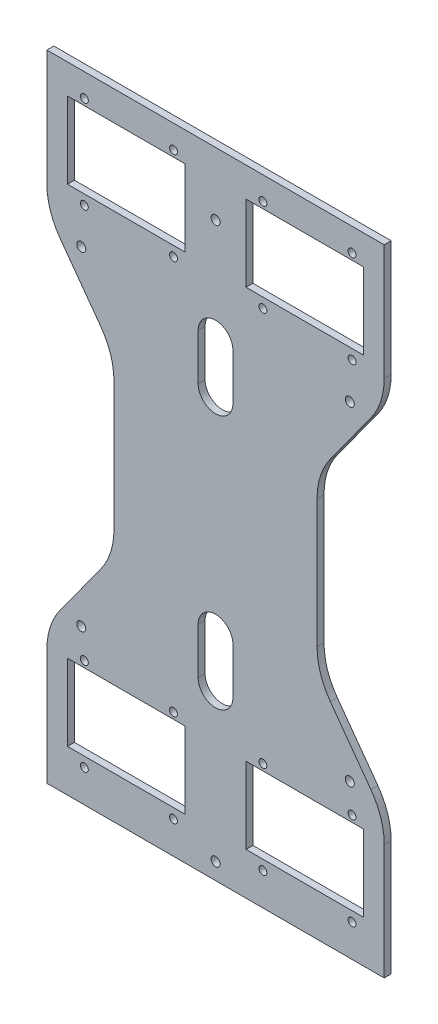
SolidWorks part; units mm, degrees
ref_plane "Alzado" through (0, 0, 0) normal (0, 0, 1) x (1, 0, 0)
ref_plane "Planta" through (0, 0, 0) normal (0, 1, 0) x (1, 0, 0)
ref_plane "Vista lateral" through (0, 0, 0) normal (1, 0, 0) x (0, 0, -1)
sketch "Croquis1" plane through (0, 0, 0) normal (0, 0, 1) x (1, 0, 0)
  line L1 (72.8628, -137.1535) -> (-72.8628, -137.1535)
  line L2 (72.8628, -137.1535) -> (72.8628, -77.4151)
  line L3 (72.8628, 137.1535) -> (-72.8628, 137.1535)
  line L4 (-72.8628, -137.1535) -> (-72.8628, -77.4151)
  line L5 (72.8628, -137.1535) -> (-72.8628, 137.1535) construction
  line L6 (72.8628, 137.1535) -> (-72.8628, -137.1535) construction
  line L7 (-72.8628, 0) -> (72.8628, 0) construction
  line L8 (0, -137.1535) -> (0, 137.1535) construction
  line L9 (-43.8628, -37.5) -> (-43.8628, 37.5)
  line L10 (-43.8628, 37.5) -> (-72.8628, 77.4151)
  line L11 (-43.8628, -37.5) -> (-72.8628, -77.4151)
  line L12 (43.8628, -37.5) -> (72.8628, -77.4151)
  line L13 (43.8628, -37.5) -> (43.8628, 37.5)
  line L14 (43.8628, 37.5) -> (72.8628, 77.4151)
  line L15 (-72.8628, 77.4151) -> (-72.8628, 137.1535)
  line L16 (72.8628, 77.4151) -> (72.8628, 137.1535)
  point P0 (0, 0)
  point P11 (0, 0)
  point P14 (-43.8628, 0)
  dimension "D1" = 145.7256
  dimension "D2" = 274.3069
  dimension "D3" = 144
  dimension "D4" = 144
  dimension "D5" = 29
  dimension "D6" = 75
  dimension "D7" = 137.1535
extrude "Saliente-Extruir1" add sketch "Croquis1" along normal blind 3
fillet "Redondeo1" radius 30 8 edges at (72.8628, 77.4151, 1.5) (43.8628, 37.5, 1.5) (43.8628, -37.5, 1.5) (72.8628, -77.4151, 1.5) (-43.8628, -37.5, 1.5) (-72.8628, -77.4151, 1.5) (-43.8628, 37.5, 1.5) (-72.8628, 77.4151, 1.5)
sketch "mid bores" plane through (0, 0, 0) normal (0, 0, 1) x (1, 0, 0)
  point P0 (-58, 71)
  point P1 (0, 110)
  point P2 (58, 71)
  point P4 (0, -130)
  point P5 (58, -71)
  point P7 (-58, -71)
  dimension "D1" = 71
  dimension "D2" = 110
  dimension "D3" = 58
  dimension "D6" = 130
  dimension "D4" = 2
  dimension "D5" = 2
sketch "Croquis2" plane through (0, 0, 3) normal (0, 0, 1) x (1, 0, 0)
  line L0 (0, 45) -> (0, 65) construction
  line L1 (-7.5, 45) -> (-7.5, 65)
  line L2 (7.5, 45) -> (7.5, 65)
  arc A0 (-7.5, 45) -> (7.5, 45) centre (0, 45) ccw
  arc A1 (7.5, 65) -> (-7.5, 65) centre (0, 65) ccw
  point P2 (0, 55)
  point P7 (-3.1499, 63.1879)
  point P8 (0, 0)
  dimension "D1" = 15
  dimension "D2" = 20
  dimension "D3" = 55
extrude "Cortar-Extruir1" cut sketch "Croquis2" against normal through all
mirror "Simetría1" about plane through (0, 0, 0) normal (0, 1, 0) of "Cortar-Extruir1"
sketch "ibt2 bores" plane through (0, 0, 3) normal (0, 0, 1) x (1, 0, 0)
  point P0 (-18.1628, 127.1535)
  point P1 (-18.1628, 87.1535)
  point P2 (-56.6628, 87.1535)
  point P3 (20.4628, 127.1535)
  point P4 (-56.6628, 127.1535)
  point P5 (20.4628, 87.1535)
  point P6 (58.9628, 87.1535)
  point P7 (58.9628, 127.1535)
  point P8 (20.4628, -123.1535)
  point P9 (58.9628, -123.1535)
  point P10 (-18.1628, -123.1535)
  point P11 (-56.6628, -123.1535)
  point P12 (-56.6628, -83.1535)
  point P13 (-18.1628, -83.1535)
  point P14 (20.4628, -83.1535)
  point P15 (58.9628, -83.1535)
hole_wizard "Taladro de margen para M31" positions "Croquis13" profile "Croquis15" hole size "M3" standard "Ansi Metric" end condition through all
sketch "Croquis13" plane through (0, 0, 3) normal (0, 0, 1) x (1, 0, 0)
  point P0 (-56.6628, 127.1535)
  point P3 (-18.1628, 127.1535)
  point P6 (-18.1628, 87.1535)
  point P9 (-56.6628, 87.1535)
  point P14 (20.4628, 127.1535)
  point P17 (20.4628, 87.1535)
  point P20 (58.9628, 87.1535)
  point P23 (58.9628, 127.1535)
  point P27 (58.9628, -123.1535)
  point P30 (20.4628, -123.1535)
  point P33 (20.4628, -83.1535)
  point P36 (58.9628, -83.1535)
  point P39 (-18.1628, -123.1535)
  point P42 (-56.6628, -123.1535)
  point P45 (-56.6628, -83.1535)
  point P48 (-18.1628, -83.1535)
sketch "Croquis15" plane through (-56.6628, 127.1535, 3) normal (1, 0, 0) x (0, -1, 0)
  line L0 (0, 0) -> (0, 3)
  line L1 (0, 3) -> (1.7, 3)
  line L2 (1.7, 3) -> (1.7, 0)
  line L5 (1.7, 0) -> (0, 0)
  line L11 (0, -6.35) -> (0, 107.95) construction
  dimension "Diámetro de taladro hasta el siguiente" = 3.4
  dimension "Profundidad de taladro hasta el siguiente" = 3
sketch "Croquis16" plane through (0, 0, 0) normal (0, 0, -1) x (-1, 0, 0)
  line L0 (13.5628, 124.0035) -> (63.5628, 124.0035) construction
  line L1 (63.5628, 124.0035) -> (63.5628, 91.8035) construction
  line L2 (63.5628, 91.8035) -> (13.5628, 91.8035) construction
  line L3 (13.5628, 91.8035) -> (13.5628, 124.0035) construction
  line L4 (-13.5628, 124.0035) -> (-13.5628, 91.8035) construction
  line L5 (-13.5628, 91.8035) -> (-63.5628, 91.8035) construction
  line L6 (-63.5628, 91.8035) -> (-63.5628, 124.0035) construction
  line L7 (-63.5628, 124.0035) -> (-13.5628, 124.0035) construction
  line L8 (-63.9628, 124.4035) -> (-13.1628, 124.4035)
  line L9 (-13.1628, 124.4035) -> (-13.1628, 91.4035)
  line L10 (-13.1628, 91.4035) -> (-63.9628, 91.4035)
  line L11 (-63.9628, 91.4035) -> (-63.9628, 124.4035)
  line L12 (13.1628, 91.4035) -> (13.1628, 124.4035)
  line L13 (13.1628, 124.4035) -> (63.9628, 124.4035)
  line L14 (63.9628, 124.4035) -> (63.9628, 91.4035)
  line L15 (63.9628, 91.4035) -> (13.1628, 91.4035)
  line L16 (63.5628, -118.5035) -> (13.5628, -118.5035) construction
  line L17 (13.5628, -118.5035) -> (13.5628, -86.3035) construction
  line L18 (13.5628, -86.3035) -> (63.5628, -86.3035) construction
  line L19 (63.5628, -86.3035) -> (63.5628, -118.5035) construction
  line L20 (-13.5628, -118.5035) -> (-13.5628, -86.3035) construction
  line L21 (-13.5628, -86.3035) -> (-63.5628, -86.3035) construction
  line L22 (-63.5628, -86.3035) -> (-63.5628, -118.5035) construction
  line L23 (-63.5628, -118.5035) -> (-13.5628, -118.5035) construction
  line L24 (63.9628, -118.9035) -> (13.1628, -118.9035)
  line L25 (13.1628, -118.9035) -> (13.1628, -85.9035)
  line L26 (13.1628, -85.9035) -> (63.9628, -85.9035)
  line L27 (63.9628, -85.9035) -> (63.9628, -118.9035)
  line L28 (-13.1628, -118.9035) -> (-13.1628, -85.9035)
  line L29 (-13.1628, -85.9035) -> (-63.9628, -85.9035)
  line L30 (-63.9628, -85.9035) -> (-63.9628, -118.9035)
  line L31 (-63.9628, -118.9035) -> (-13.1628, -118.9035)
  dimension "D1" = 0.4
  dimension "D2" = 0.4
extrude "Cortar-Extruir2" cut sketch "Croquis16" against normal through all
hole_wizard "Taladro de margen para M3.51" positions "Croquis17" profile "Croquis18" hole size "M3.5" standard "Ansi Metric" end condition through all
sketch "Croquis17" plane through (0, 0, 3) normal (0, 0, 1) x (1, 0, 0)
  point P0 (-58, 71)
  point P3 (0, 110)
  point P6 (-58, -71)
  point P9 (0, -130)
  point P12 (58, -71)
  point P15 (58, 71)
sketch "Croquis18" plane through (-58, 71, 3) normal (1, 0, 0) x (0, -1, 0)
  line L0 (0, 0) -> (0, 3)
  line L1 (0, 3) -> (1.95, 3)
  line L2 (1.95, 3) -> (1.95, 0)
  line L5 (1.95, 0) -> (0, 0)
  line L11 (0, -6.35) -> (0, 107.95) construction
  dimension "Diámetro de taladro hasta el siguiente" = 3.9
  dimension "Profundidad de taladro hasta el siguiente" = 3
